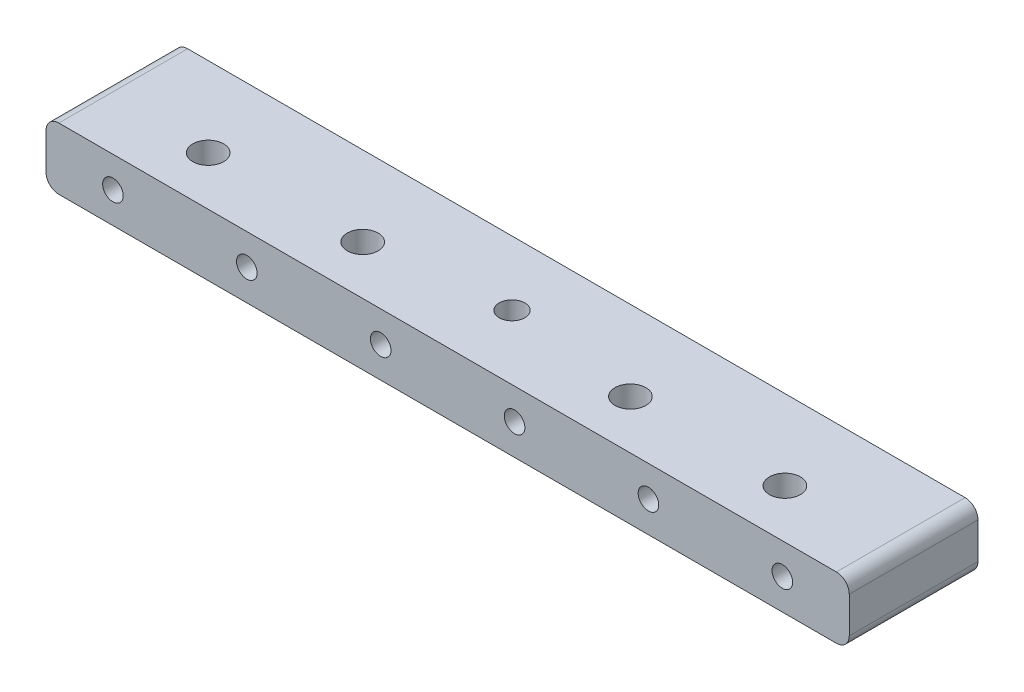
SolidWorks part; units mm, degrees
material "Alumina"
ref_plane "Front Plane" through (0, 0, 0) normal (0, 0, 1) x (1, 0, 0)
ref_plane "Top Plane" through (0, 0, 0) normal (0, 1, 0) x (1, 0, 0)
ref_plane "Right Plane" through (0, 0, 0) normal (1, 0, 0) x (0, 0, -1)
sketch "Sketch1" plane through (0, 0, 0) normal (0, 1, 0) x (1, 0, 0)
  line L0 (-78, -3) -> (78, -3) construction
  line L1 (-78, 12.5) -> (78, 12.5)
  line L2 (-78, 12.5) -> (-78, -12.5)
  line L3 (-78, -12.5) -> (78, -12.5)
  line L4 (78, 12.5) -> (78, -12.5)
  line L5 (-78, 12.5) -> (78, -12.5) construction
  line L6 (-78, -12.5) -> (78, 12.5) construction
  line L7 (0, 0) -> (0, -50000) construction
  circle A0 centre (0, 0) radius 2.5
  circle A1 centre (-56, -3) radius 3
  circle A2 centre (-26, -3) radius 3
  circle A3 centre (56, -3) radius 3
  circle A4 centre (26, -3) radius 3
  point P0 (0, 0)
  dimension "D4" = 5
  dimension "D6" = 6
  dimension "D1" = 25
  dimension "D2" = 156
  dimension "D3" = 9.5
  dimension "D5" = 30
  dimension "26" = 26
extrude "Boss-Extrude1" add sketch "Sketch1" along normal mid plane 12
cosmetic thread "Cosmetic Thread13" parameters "D2"=6
fillet "Fillet1" radius 2.5 4 edges at (-78, -6, 0) (-78, 6, 0) (78, -6, 0) (78, 6, 0)
sketch "Sketch2" plane through (0, 0, 12.5) normal (0, 0, 1) x (1, 0, 0)
  line L0 (0, 0) -> (-50000, 0) construction
  circle A0 centre (-65, 0) radius 2
  dimension "D1" = 4
  dimension "D2" = 65
extrude "Cut-Extrude1" cut sketch "Sketch2" against normal blind 10
cosmetic thread "Cosmetic Thread1" parameters "D2"=5
pattern_linear "LPattern1" count 6 spacing 26 along (1, 0, 0) of "Cut-Extrude1"
cosmetic thread "Cosmetic Thread2" parameters "D2"=5
cosmetic thread "Cosmetic Thread3" parameters "D2"=5
cosmetic thread "Cosmetic Thread4" parameters "D2"=5
cosmetic thread "Cosmetic Thread5" parameters "D2"=5
cosmetic thread "Cosmetic Thread6" parameters "D2"=5
mirror "Mirror1" about plane through (0, 0, 0) normal (0, 0, 1) of "LPattern1", "Cut-Extrude1"
cosmetic thread "Cosmetic Thread7" parameters "D2"=5
cosmetic thread "Cosmetic Thread8" parameters "D2"=5
cosmetic thread "Cosmetic Thread9" parameters "D2"=5
cosmetic thread "Cosmetic Thread10" parameters "D2"=5
cosmetic thread "Cosmetic Thread11" parameters "D2"=5
cosmetic thread "Cosmetic Thread12" parameters "D2"=5
